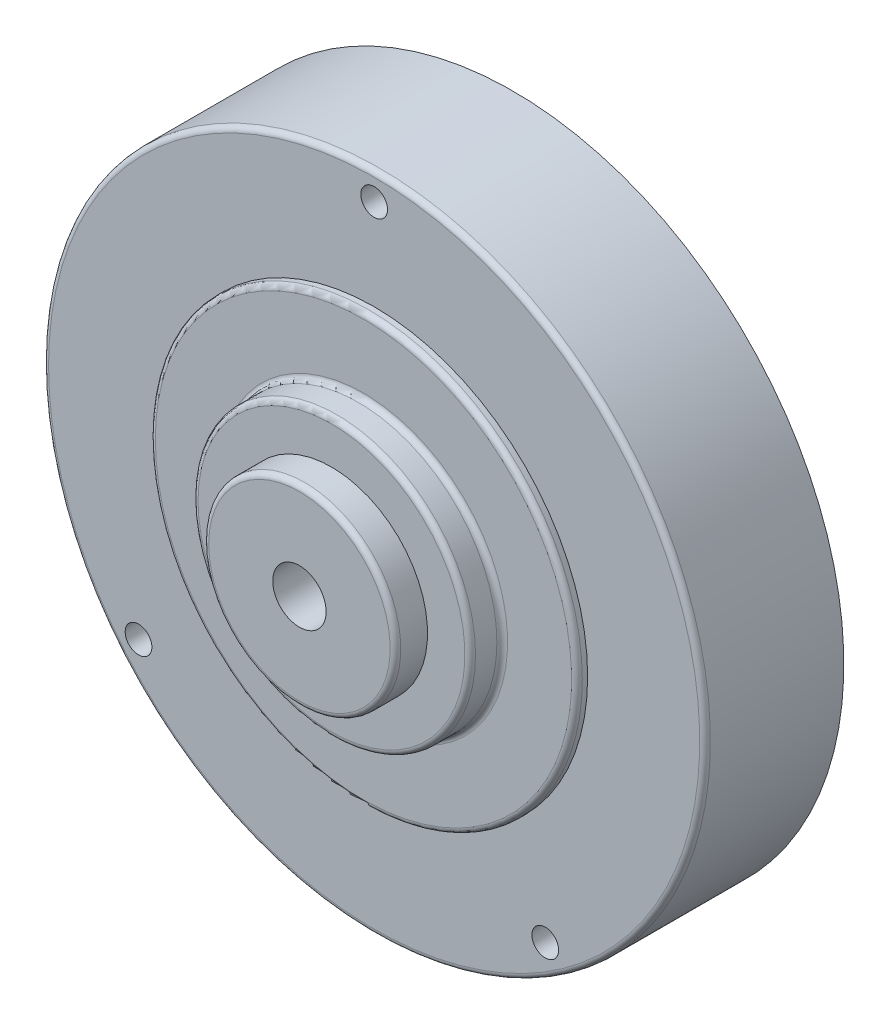
SolidWorks part; units mm, degrees
ref_plane "Plan de face" through (0, 0, 0) normal (0, 0, 1) x (1, 0, 0)
ref_plane "Plan de dessus" through (0, 0, 0) normal (0, 1, 0) x (1, 0, 0)
ref_plane "Plan de droite" through (0, 0, 0) normal (1, 0, 0) x (0, 0, -1)
sketch "Esquisse1" plane through (0, 0, 0) normal (0, 1, 0) x (1, 0, 0)
  line L0 (0, 0) -> (31, 0)
  line L1 (31, 0) -> (31, -13)
  line L2 (31, -13) -> (20, -13)
  line L3 (20, -13) -> (20, -14)
  line L4 (20, -14) -> (13, -14)
  line L5 (13, -14) -> (13, -17)
  line L6 (13, -17) -> (9, -17)
  line L7 (9, -17) -> (9, -20)
  line L8 (9, -20) -> (0, -20)
  line L9 (0, 0) -> (0, -20) construction
  line L10 (0, 0) -> (0, -20)
  dimension "D1" = 31
  dimension "D2" = 13
  dimension "D3" = 1
  dimension "D4" = 3
  dimension "D5" = 3
  dimension "D6" = 20
  dimension "D7" = 13
  dimension "D8" = 9
revolve "Révolution1" add sketch "Esquisse1" angle 360 about L9
sketch "Esquisse2" plane through (0, 0, 20) normal (0, 0, 1) x (1, 0, 0)
  circle A0 centre (0, 0) radius 2.5
  dimension "D1" = 5
extrude "Enlèv. mat.-Extru.1" cut sketch "Esquisse2" against normal through all
fillet "Congé1" radius 0.5 5 edges at (-9, 0, 20) (-13, 0, 17) (-13, 0, 14) (-20, 0, 14) (-31, 0, 13)
sketch "Esquisse3" plane through (0, 0, 13) normal (0, 0, 1) x (1, 0, 0)
  line L0 (0, 28.5) -> (0, 0) construction
  line L1 (0, 0) -> (-22.0713, -18.0307) construction
  line L2 (0, 0) -> (16.0288, -23.5654) construction
  circle A0 centre (0, 28.5) radius 1.25
  circle A1 centre (-22.0713, -18.0307) radius 1.25
  circle A2 centre (16.0288, -23.5654) radius 1.25
  dimension "D2" = 2.5
  dimension "D1" = 28.5
  dimension "D3" = 38.5
  dimension "D4" = 51.5
  dimension "D5" = 54.4769
extrude "Enlèv. mat.-Extru.2" cut sketch "Esquisse3" against normal blind 5
